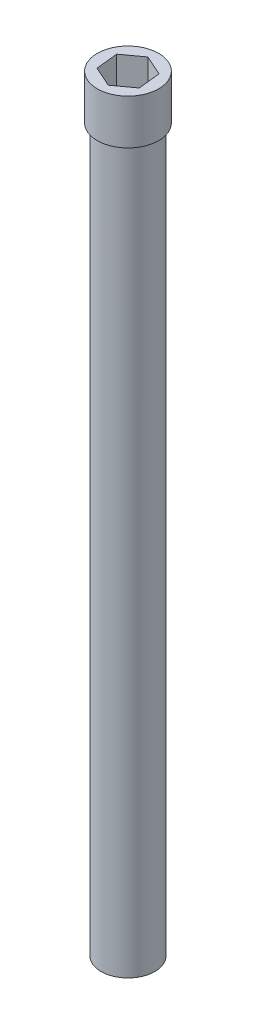
SolidWorks part; units mm, degrees
ref_plane "Front Plane" through (0, 0, 0) normal (0, 0, 1) x (1, 0, 0)
ref_plane "Top Plane" through (0, 0, 0) normal (0, 1, 0) x (1, 0, 0)
ref_plane "Right Plane" through (0, 0, 0) normal (1, 0, 0) x (0, 0, -1)
sketch "Sketch1" plane through (0, 0, 0) normal (0, 1, 0) x (1, 0, 0)
  circle A0 centre (0, 0) radius 3
  dimension "D1" = 6
extrude "Boss-Extrude1" add sketch "Sketch1" along normal blind 30
sketch "Sketch2" plane through (0, 30, 0) normal (0, 1, 0) x (1, 0, 0)
  circle A0 centre (0, 0) radius 3.4205
extrude "Boss-Extrude2" add sketch "Sketch2" along normal blind 5
sketch "Sketch3" plane through (0, 35, 0) normal (0, 1, 0) x (1, 0, 0)
  line L1 (-0.2588, 2.4623) -> (-2.2618, 1.007)
  line L2 (-2.2618, 1.007) -> (-2.003, -1.4552)
  line L3 (-2.003, -1.4552) -> (0.2588, -2.4623)
  line L4 (0.2588, -2.4623) -> (2.2618, -1.007)
  line L5 (2.2618, -1.007) -> (2.003, 1.4552)
  line L6 (2.003, 1.4552) -> (-0.2588, 2.4623)
  circle A0 centre (0, 0) radius 2.1441 construction
extrude "Cut-Extrude1" cut sketch "Sketch3" against normal blind 4
sketch "Sketch4" plane through (0, 0, 0) normal (0, -1, 0) x (-1, 0, 0)
  circle A0 centre (0, 0) radius 3
  dimension "D1" = 6
extrude "Boss-Extrude3" add sketch "Sketch4" along normal blind 50.3608
